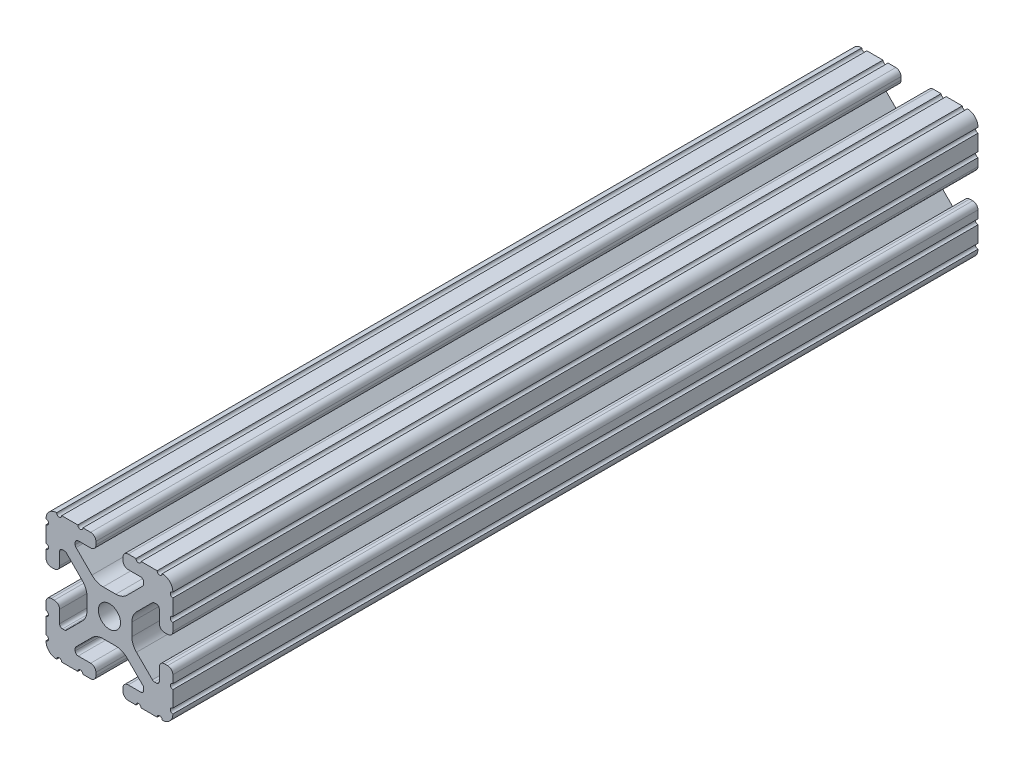
SolidWorks part; units mm, degrees
material "6105-T5 Aluminum"
ref_plane "Front Plane" through (0, 0, 0) normal (0, 0, 1) x (1, 0, 0)
ref_plane "Top Plane" through (0, 0, 0) normal (0, 1, 0) x (1, 0, 0)
ref_plane "Right Plane" through (0, 0, 0) normal (1, 0, 0) x (0, 0, -1)
sketch "Sketch1" plane through (0, 0, 0) normal (0, 0, 1) x (1, 0, 0)
  line L0 (-14.097, 10.287) -> (-13.5289, 10.287)
  line L1 (-12.9003, 10.0266) -> (-8.1292, 5.2555)
  line L2 (-6.738, 1.8969) -> (-6.738, -1.8969)
  line L3 (-8.1292, -5.2555) -> (-12.9003, -10.0266)
  line L4 (-13.5289, -10.287) -> (-14.097, -10.287)
  line L5 (-14.986, -9.398) -> (-14.986, -5.6388)
  line L6 (-16.5608, -4.064) -> (-17.4752, -4.064)
  line L7 (-19.05, -5.6388) -> (-19.05, -7.9756)
  line L8 (-19.05, -9.4996) -> (-19.05, -14.3256)
  line L9 (-19.05, -15.8496) -> (-19.05, -15.875)
  line L10 (-15.875, -19.05) -> (-15.8496, -19.05)
  line L11 (-14.3256, -19.05) -> (-9.4996, -19.05)
  line L12 (-7.9756, -19.05) -> (-5.6388, -19.05)
  line L13 (-4.064, -17.4752) -> (-4.064, -16.5608)
  line L14 (-5.6388, -14.986) -> (-9.398, -14.986)
  line L15 (-10.287, -14.097) -> (-10.287, -13.5289)
  line L16 (-10.0266, -12.9003) -> (-5.2555, -8.1292)
  line L17 (-1.8969, -6.738) -> (1.8969, -6.738)
  line L18 (5.2555, -8.1292) -> (10.0266, -12.9003)
  line L19 (10.287, -13.5289) -> (10.287, -14.097)
  line L20 (9.398, -14.986) -> (5.6388, -14.986)
  line L21 (4.064, -16.5608) -> (4.064, -17.4752)
  line L22 (5.6388, -19.05) -> (7.9756, -19.05)
  line L23 (9.4996, -19.05) -> (14.3256, -19.05)
  line L24 (15.8496, -19.05) -> (15.875, -19.05)
  line L25 (19.05, -15.875) -> (19.05, -15.8496)
  line L26 (19.05, -14.3256) -> (19.05, -9.4996)
  line L27 (19.05, -7.9756) -> (19.05, -5.6388)
  line L28 (17.4752, -4.064) -> (16.5608, -4.064)
  line L29 (14.986, -5.6388) -> (14.986, -9.398)
  line L30 (14.097, -10.287) -> (13.5289, -10.287)
  line L31 (12.9003, -10.0266) -> (8.1292, -5.2555)
  line L32 (6.738, -1.8969) -> (6.738, 1.8969)
  line L33 (8.1292, 5.2555) -> (12.9003, 10.0266)
  line L34 (13.5289, 10.287) -> (14.097, 10.287)
  line L35 (14.986, 9.398) -> (14.986, 5.6388)
  line L36 (16.5608, 4.064) -> (17.4752, 4.064)
  line L37 (19.05, 5.6388) -> (19.05, 7.9756)
  line L38 (19.05, 9.4996) -> (19.05, 14.3256)
  line L39 (19.05, 15.8496) -> (19.05, 15.875)
  line L40 (15.875, 19.05) -> (15.8496, 19.05)
  line L41 (14.3256, 19.05) -> (9.4996, 19.05)
  line L42 (7.9756, 19.05) -> (5.6388, 19.05)
  line L43 (4.064, 17.4752) -> (4.064, 16.5608)
  line L44 (5.6388, 14.986) -> (9.398, 14.986)
  line L45 (10.287, 14.097) -> (10.287, 13.5289)
  line L46 (10.0266, 12.9003) -> (5.2555, 8.1292)
  line L47 (1.8969, 6.738) -> (-1.8969, 6.738)
  line L48 (-5.2555, 8.1292) -> (-10.0266, 12.9003)
  line L49 (-10.287, 13.5289) -> (-10.287, 14.097)
  line L50 (-9.398, 14.986) -> (-5.6388, 14.986)
  line L51 (-4.064, 16.5608) -> (-4.064, 17.4752)
  line L52 (-5.6388, 19.05) -> (-7.9756, 19.05)
  line L53 (-9.4996, 19.05) -> (-14.3256, 19.05)
  line L54 (-15.8496, 19.05) -> (-15.875, 19.05)
  line L55 (-19.05, 15.875) -> (-19.05, 15.8496)
  line L56 (-19.05, 14.3256) -> (-19.05, 9.4996)
  line L57 (-19.05, 7.9756) -> (-19.05, 5.6388)
  line L58 (-17.4752, 4.064) -> (-16.5608, 4.064)
  line L59 (-14.986, 5.6388) -> (-14.986, 9.398)
  circle A0 centre (0, 0) radius 3.3274
  arc A1 (-14.097, 10.287) -> (-14.986, 9.398) centre (-14.097, 9.398) ccw
  arc A2 (-12.9003, 10.0266) -> (-13.5289, 10.287) centre (-13.5289, 9.398) ccw
  arc A3 (-6.738, 1.8969) -> (-8.1292, 5.2555) centre (-11.4878, 1.8969) ccw
  arc A4 (-8.1292, -5.2555) -> (-6.738, -1.8969) centre (-11.4878, -1.8969) ccw
  arc A5 (-13.5289, -10.287) -> (-12.9003, -10.0266) centre (-13.5289, -9.398) ccw
  arc A6 (-14.986, -9.398) -> (-14.097, -10.287) centre (-14.097, -9.398) ccw
  arc A7 (-14.986, -5.6388) -> (-16.5608, -4.064) centre (-16.5608, -5.6388) ccw
  arc A8 (-17.4752, -4.064) -> (-19.05, -5.6388) centre (-17.4752, -5.6388) ccw
  arc A9 (-19.05, -9.4996) -> (-19.05, -7.9756) centre (-19.05, -8.7376) ccw
  arc A10 (-19.05, -15.8496) -> (-19.05, -14.3256) centre (-19.05, -15.0876) ccw
  arc A11 (-19.05, -15.875) -> (-15.875, -19.05) centre (-15.875, -15.875) ccw
  arc A12 (-14.3256, -19.05) -> (-15.8496, -19.05) centre (-15.0876, -19.05) ccw
  arc A13 (-7.9756, -19.05) -> (-9.4996, -19.05) centre (-8.7376, -19.05) ccw
  arc A14 (-5.6388, -19.05) -> (-4.064, -17.4752) centre (-5.6388, -17.4752) ccw
  arc A15 (-4.064, -16.5608) -> (-5.6388, -14.986) centre (-5.6388, -16.5608) ccw
  arc A16 (-10.287, -14.097) -> (-9.398, -14.986) centre (-9.398, -14.097) ccw
  arc A17 (-10.0266, -12.9003) -> (-10.287, -13.5289) centre (-9.398, -13.5289) ccw
  arc A18 (-1.8969, -6.738) -> (-5.2555, -8.1292) centre (-1.8969, -11.4878) ccw
  arc A19 (5.2555, -8.1292) -> (1.8969, -6.738) centre (1.8969, -11.4878) ccw
  arc A20 (10.287, -13.5289) -> (10.0266, -12.9003) centre (9.398, -13.5289) ccw
  arc A21 (9.398, -14.986) -> (10.287, -14.097) centre (9.398, -14.097) ccw
  arc A22 (5.6388, -14.986) -> (4.064, -16.5608) centre (5.6388, -16.5608) ccw
  arc A23 (4.064, -17.4752) -> (5.6388, -19.05) centre (5.6388, -17.4752) ccw
  arc A24 (9.4996, -19.05) -> (7.9756, -19.05) centre (8.7376, -19.05) ccw
  arc A25 (15.8496, -19.05) -> (14.3256, -19.05) centre (15.0876, -19.05) ccw
  arc A26 (15.875, -19.05) -> (19.05, -15.875) centre (15.875, -15.875) ccw
  arc A27 (19.05, -14.3256) -> (19.05, -15.8496) centre (19.05, -15.0876) ccw
  arc A28 (19.05, -7.9756) -> (19.05, -9.4996) centre (19.05, -8.7376) ccw
  arc A29 (19.05, -5.6388) -> (17.4752, -4.064) centre (17.4752, -5.6388) ccw
  arc A30 (16.5608, -4.064) -> (14.986, -5.6388) centre (16.5608, -5.6388) ccw
  arc A31 (14.097, -10.287) -> (14.986, -9.398) centre (14.097, -9.398) ccw
  arc A32 (12.9003, -10.0266) -> (13.5289, -10.287) centre (13.5289, -9.398) ccw
  arc A33 (6.738, -1.8969) -> (8.1292, -5.2555) centre (11.4878, -1.8969) ccw
  arc A34 (8.1292, 5.2555) -> (6.738, 1.8969) centre (11.4878, 1.8969) ccw
  arc A35 (13.5289, 10.287) -> (12.9003, 10.0266) centre (13.5289, 9.398) ccw
  arc A36 (14.986, 9.398) -> (14.097, 10.287) centre (14.097, 9.398) ccw
  arc A37 (14.986, 5.6388) -> (16.5608, 4.064) centre (16.5608, 5.6388) ccw
  arc A38 (17.4752, 4.064) -> (19.05, 5.6388) centre (17.4752, 5.6388) ccw
  arc A39 (19.05, 9.4996) -> (19.05, 7.9756) centre (19.05, 8.7376) ccw
  arc A40 (19.05, 15.8496) -> (19.05, 14.3256) centre (19.05, 15.0876) ccw
  arc A41 (19.05, 15.875) -> (15.875, 19.05) centre (15.875, 15.875) ccw
  arc A42 (14.3256, 19.05) -> (15.8496, 19.05) centre (15.0876, 19.05) ccw
  arc A43 (7.9756, 19.05) -> (9.4996, 19.05) centre (8.7376, 19.05) ccw
  arc A44 (5.6388, 19.05) -> (4.064, 17.4752) centre (5.6388, 17.4752) ccw
  arc A45 (4.064, 16.5608) -> (5.6388, 14.986) centre (5.6388, 16.5608) ccw
  arc A46 (10.287, 14.097) -> (9.398, 14.986) centre (9.398, 14.097) ccw
  arc A47 (10.0266, 12.9003) -> (10.287, 13.5289) centre (9.398, 13.5289) ccw
  arc A48 (1.8969, 6.738) -> (5.2555, 8.1292) centre (1.8969, 11.4878) ccw
  arc A49 (-5.2555, 8.1292) -> (-1.8969, 6.738) centre (-1.8969, 11.4878) ccw
  arc A50 (-10.287, 13.5289) -> (-10.0266, 12.9003) centre (-9.398, 13.5289) ccw
  arc A51 (-9.398, 14.986) -> (-10.287, 14.097) centre (-9.398, 14.097) ccw
  arc A52 (-5.6388, 14.986) -> (-4.064, 16.5608) centre (-5.6388, 16.5608) ccw
  arc A53 (-4.064, 17.4752) -> (-5.6388, 19.05) centre (-5.6388, 17.4752) ccw
  arc A54 (-9.4996, 19.05) -> (-7.9756, 19.05) centre (-8.7376, 19.05) ccw
  arc A55 (-15.8496, 19.05) -> (-14.3256, 19.05) centre (-15.0876, 19.05) ccw
  arc A56 (-15.875, 19.05) -> (-19.05, 15.875) centre (-15.875, 15.875) ccw
  arc A57 (-19.05, 14.3256) -> (-19.05, 15.8496) centre (-19.05, 15.0876) ccw
  arc A58 (-19.05, 7.9756) -> (-19.05, 9.4996) centre (-19.05, 8.7376) ccw
  arc A59 (-19.05, 5.6388) -> (-17.4752, 4.064) centre (-17.4752, 5.6388) ccw
  arc A60 (-16.5608, 4.064) -> (-14.986, 5.6388) centre (-16.5608, 5.6388) ccw
extrude "Boss-Extrude1" add sketch "Sketch1" along normal blind 241.808
